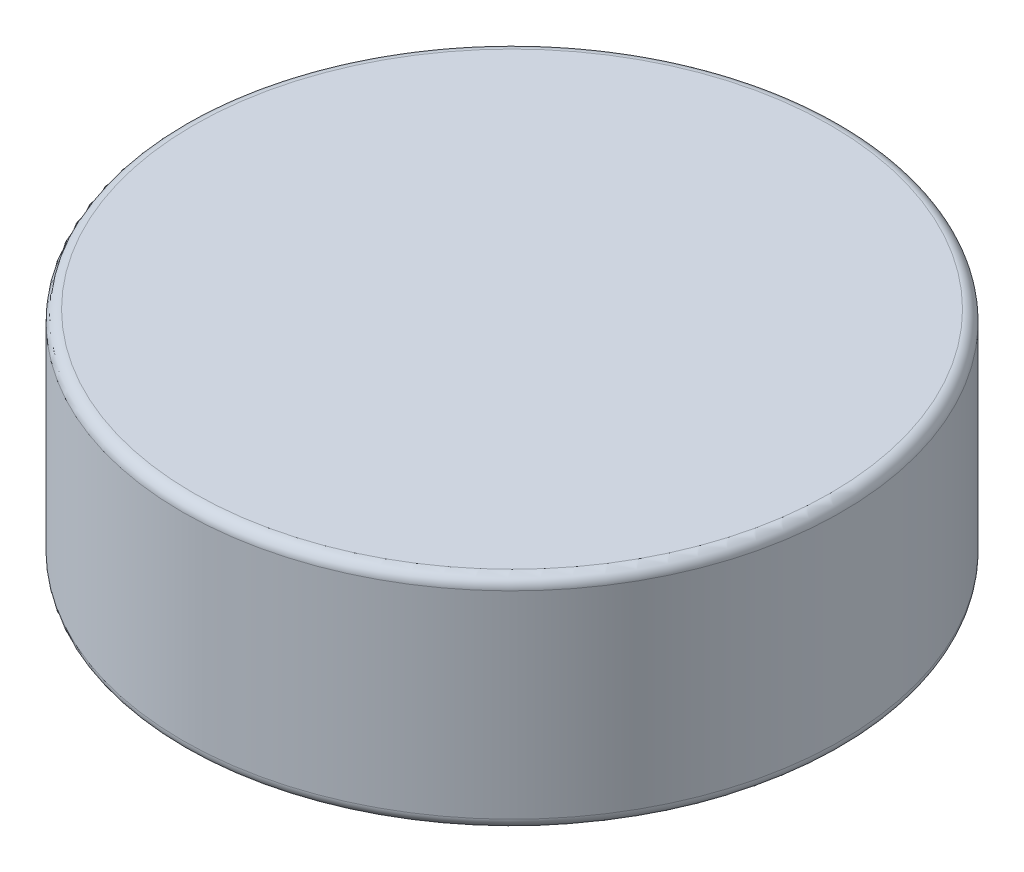
SolidWorks part; units mm, degrees
ref_plane "前视基准面" through (0, 0, 0) normal (0, 0, 1) x (1, 0, 0)
ref_plane "上视基准面" through (0, 0, 0) normal (0, 1, 0) x (1, 0, 0)
ref_plane "右视基准面" through (0, 0, 0) normal (1, 0, 0) x (0, 0, -1)
sketch "草图1" plane through (0, 0, 0) normal (0, 1, 0) x (1, 0, 0)
  circle A0 centre (0, 0) radius 3
  dimension "D1" = 6
extrude "凸台-拉伸1" add sketch "草图1" along normal blind 2
fillet "圆角1" radius 0.1 2 edges at (0, 0, 3) (0, 2, 3)
